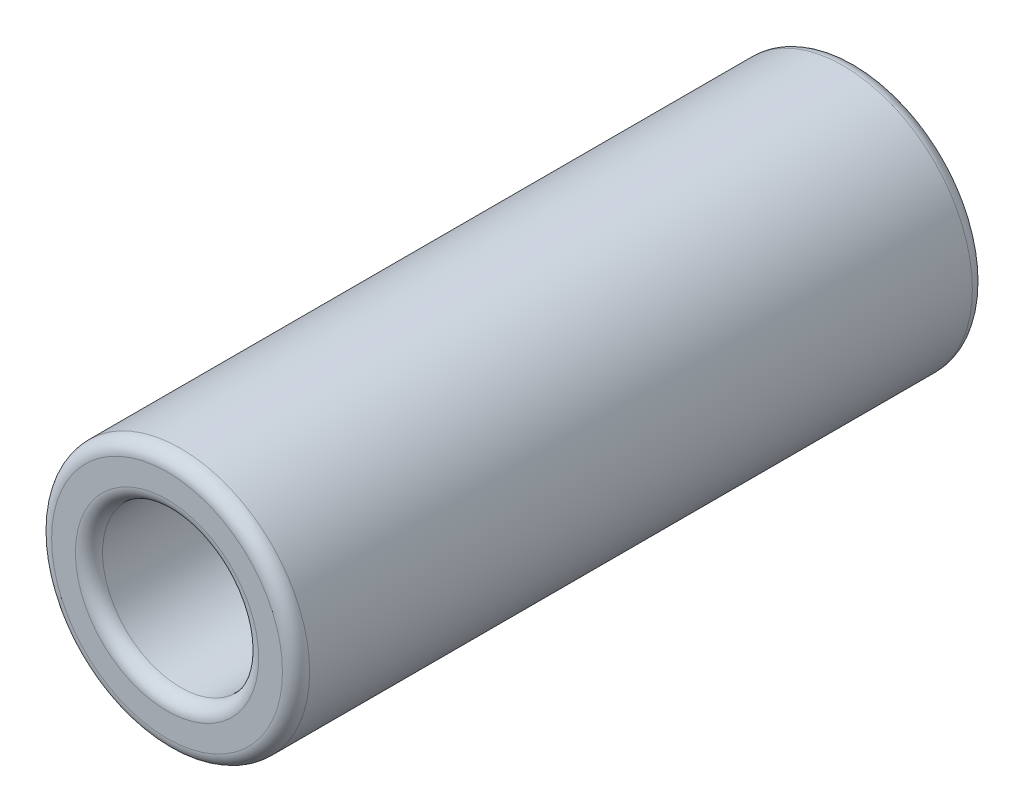
SolidWorks part; units mm, degrees
ref_plane "Plan de face" through (0, 0, 0) normal (0, 0, 1) x (1, 0, 0)
ref_plane "Plan de dessus" through (0, 0, 0) normal (0, 1, 0) x (1, 0, 0)
ref_plane "Plan de droite" through (0, 0, 0) normal (1, 0, 0) x (0, 0, -1)
sketch "Esquisse1" plane through (0, 0, 0) normal (0, 0, 1) x (1, 0, 0)
  circle A0 centre (0, 0) radius 9.5
extrude "Extrusion1" add sketch "Esquisse1" along normal blind 50.8
sketch "Esquisse2" plane through (0, 0, 50.8) normal (0, 0, 1) x (1, 0, 0)
  circle A0 centre (0, 0) radius 5.75
extrude "Extrusion2" cut sketch "Esquisse2" against normal through all
fillet "Fillet1" radius 1 4 edges at (5.75, 0, 0) (9.5, 0, 0) (5.75, 0, 50.8) (9.5, 0, 50.8)
ref_plane "Plane1" through (0, 0, 25.4) normal (0, 0, 1) x (1, 0, 0)
